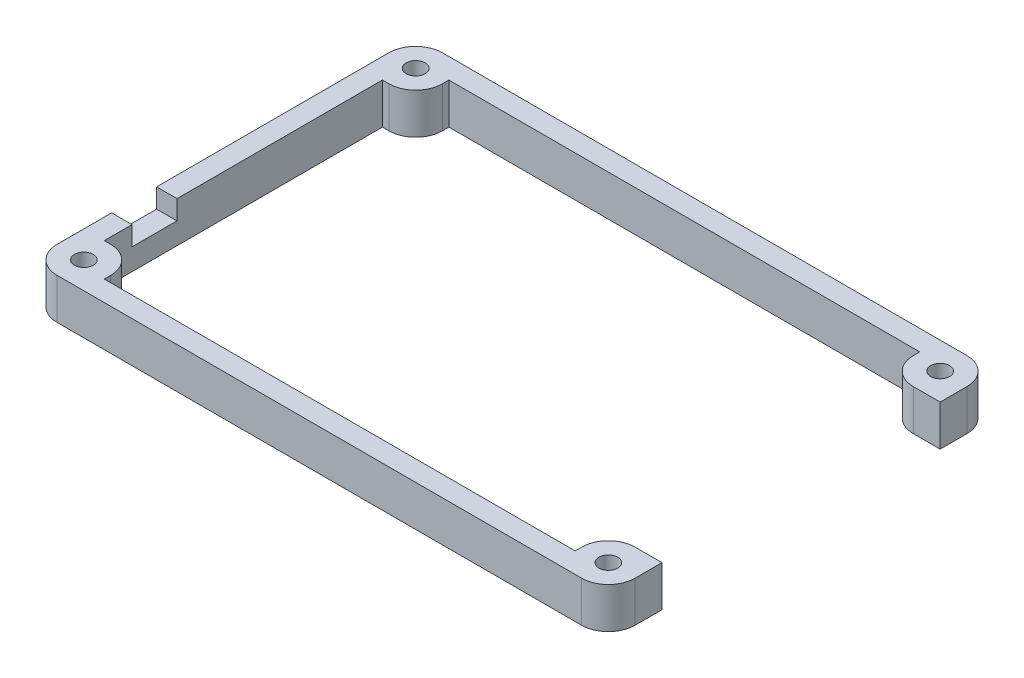
SolidWorks part; units mm, degrees
material "Rubber"
ref_plane "Front" through (0, 0, 0) normal (0, 0, 1) x (1, 0, 0)
ref_plane "Top" through (0, 0, 0) normal (0, 1, 0) x (1, 0, 0)
ref_plane "Right" through (0, 0, 0) normal (1, 0, 0) x (0, 0, -1)
sketch "Sketch1" plane through (0, 0, 0) normal (0, 1, 0) x (1, 0, 0)
  line L0 (-45, 0) -> (45, 0) construction
  line L1 (-45, 30) -> (45, 30) construction
  line L2 (-45, 30) -> (-45, -30) construction
  line L3 (-45, -30) -> (45, -30) construction
  line L4 (45, 30) -> (45, -30) construction
  line L5 (0, -30) -> (0, 30) construction
  line L6 (41.825, 26.825) -> (41.825, -26.825) construction
  line L7 (-41.825, -26.825) -> (41.825, -26.825) construction
  line L8 (-41.825, 26.825) -> (-41.825, -26.825) construction
  line L9 (-41.825, 26.825) -> (41.825, 26.825) construction
  line L10 (40.825, 25.825) -> (40.825, -25.825) construction
  line L11 (-40.825, -25.825) -> (40.825, -25.825) construction
  line L12 (-40.825, 25.825) -> (-40.825, -25.825) construction
  line L13 (-40.825, 25.825) -> (40.825, 25.825) construction
  line L14 (40.825, 21.65) -> (45, 21.65) construction
  line L15 (40.825, -21.65) -> (45, -21.65) construction
  line L16 (36.65, -25.825) -> (36.65, -30) construction
  line L17 (-36.65, -25.825) -> (-36.65, -30) construction
  line L18 (-40.825, -21.65) -> (-45, -21.65) construction
  line L19 (-36.65, 25.825) -> (-36.65, 30) construction
  line L20 (-40.825, 21.65) -> (-45, 21.65) construction
  line L21 (36.65, 25.825) -> (36.65, 30) construction
  line L22 (40.825, -25.825) -> (41.825, -25.825) construction
  circle A0 centre (-40.825, -25.825) radius 1 construction
  circle A1 centre (40.825, -25.825) radius 1 construction
  circle A2 centre (40.825, 25.825) radius 1 construction
  circle A3 centre (-40.825, 25.825) radius 1 construction
  circle A4 centre (40.825, -25.825) radius 4.175 construction
  circle A5 centre (40.825, 25.825) radius 4.175 construction
  circle A6 centre (-40.825, 25.825) radius 4.175 construction
  circle A7 centre (-40.825, -25.825) radius 4.175 construction
  dimension "D1" = 90
  dimension "D2" = 60
  dimension "D4" = 1
  dimension "D3" = 3.175
sketch "Sketch2" plane through (0, 0, 0) normal (0, 1, 0) x (1, 0, 0)
  line L0 (-45, 30) -> (-45, -30) construction
  line L1 (-45, -30) -> (45, -30) construction
  line L2 (45, 30) -> (45, -30) construction
  line L3 (-45, 30) -> (45, 30) construction
  line L4 (40.825, 21.65) -> (45, 21.65) construction
  line L5 (36.65, 25.825) -> (36.65, 30) construction
  line L6 (-36.65, 25.825) -> (-36.65, 30) construction
  line L7 (-40.825, 21.65) -> (-45, 21.65) construction
  line L8 (-36.65, -25.825) -> (-36.65, -30) construction
  line L9 (-40.825, -21.65) -> (-45, -21.65) construction
  line L10 (36.65, -25.825) -> (36.65, -30) construction
  line L11 (40.825, -21.65) -> (45, -21.65) construction
  line L16 (-45, 25.825) -> (-45, -25.825)
  line L17 (-40.825, -30) -> (40.825, -30)
  line L18 (45, 25.825) -> (45, -25.825)
  line L19 (-40.825, 30) -> (40.825, 30)
  line L20 (40.825, 21.65) -> (41.825, 21.65)
  line L21 (36.65, 25.825) -> (36.65, 26.825)
  line L22 (-36.65, 25.825) -> (-36.65, 26.825)
  line L23 (-40.825, 21.65) -> (-41.825, 21.65)
  line L24 (-36.65, -25.825) -> (-36.65, -26.825)
  line L25 (-40.825, -21.65) -> (-41.825, -21.65)
  line L26 (36.65, -25.825) -> (36.65, -26.825)
  line L27 (40.825, -21.65) -> (41.825, -21.65)
  line L28 (41.825, 26.825) -> (41.825, -26.825) construction
  line L29 (-36.65, -26.825) -> (36.65, -26.825)
  line L30 (-41.825, 26.825) -> (41.825, 26.825) construction
  line L31 (-41.825, 26.825) -> (-41.825, -26.825) construction
  line L32 (-36.65, 26.825) -> (36.65, 26.825)
  line L33 (-41.825, 21.65) -> (-41.825, -21.65)
  line L34 (41.825, 21.65) -> (41.825, -21.65)
  line L35 (-41.825, -26.825) -> (41.825, -26.825) construction
  circle A0 centre (40.825, 25.825) radius 4.175 construction
  circle A1 centre (40.825, 25.825) radius 1 construction
  circle A2 centre (-40.825, 25.825) radius 4.175 construction
  circle A3 centre (-40.825, 25.825) radius 1 construction
  circle A4 centre (-40.825, -25.825) radius 4.175 construction
  circle A5 centre (40.825, -25.825) radius 4.175 construction
  arc A6 (45, 25.825) -> (40.825, 30) centre (40.825, 25.825) ccw
  circle A7 centre (40.825, 25.825) radius 1 construction
  arc A8 (-40.825, 30) -> (-45, 25.825) centre (-40.825, 25.825) ccw
  circle A9 centre (-40.825, 25.825) radius 1 construction
  arc A10 (-36.65, -25.825) -> (-40.825, -21.65) centre (-40.825, -25.825) ccw
  arc A11 (40.825, -21.65) -> (36.65, -25.825) centre (40.825, -25.825) ccw
  circle A12 centre (-40.825, -25.825) radius 1 construction
  circle A13 centre (40.825, -25.825) radius 1 construction
  circle A14 centre (-40.825, -25.825) radius 1 construction
  circle A15 centre (40.825, -25.825) radius 1 construction
  arc A16 (-40.825, 21.65) -> (-36.65, 25.825) centre (-40.825, 25.825) ccw
  arc A17 (-45, -25.825) -> (-40.825, -30) centre (-40.825, -25.825) ccw
  arc A18 (40.825, -30) -> (45, -25.825) centre (40.825, -25.825) ccw
  arc A19 (36.65, 25.825) -> (40.825, 21.65) centre (40.825, 25.825) ccw
extrude "Boss-Extrude3" add sketch "Sketch2" along normal blind 6.35
sketch "Antenna Hole Size" plane through (-45, 0, 0) normal (-1, 0, 0) x (0, 0, 1)
  line L0 (13.825, 6.35) -> (25.825, 6.35) construction
  line L1 (25.825, 6.35) -> (25.825, 0) construction
  line L3 (10.325, 9.35) -> (17.325, 9.35)
  line L4 (10.325, 9.35) -> (10.325, 3.35)
  line L5 (10.325, 3.35) -> (17.325, 3.35)
  line L6 (17.325, 9.35) -> (17.325, 3.35)
  line L7 (10.325, 9.35) -> (17.325, 3.35) construction
  line L8 (10.325, 3.35) -> (17.325, 9.35) construction
  dimension "D1" = 12
  dimension "D2" = 6
  dimension "D3" = 7
extrude "Cut-Extrude3" cut sketch "Antenna Hole Size" against normal up to surface (3.175 mm away) up to face at (-41.825, 3.175, 0)
sketch "Sketch7" plane through (0, 0, 0) normal (0, -1, 0) x (1, 0, 0)
  circle A0 centre (-40.825, -25.825) radius 1.4732
  circle A1 centre (-40.825, 25.825) radius 1.4732
  circle A2 centre (40.825, 25.825) radius 1.4732
  circle A3 centre (40.825, -25.825) radius 1.4732
  dimension "D1" = 2.9464
  dimension "D2" = 2.9464
  dimension "D3" = 2.9464
  dimension "D4" = 2.9464
extrude "Cut-Extrude4" cut sketch "Sketch7" against normal blind 10
sketch "Sketch8" plane through (0, 6.35, 0) normal (0, 1, 0) x (1, 0, 0)
  line L0 (45, -25.825) -> (45, 25.825) construction
  line L1 (45, 21.65) -> (41.825, 21.65)
  line L2 (45, 21.65) -> (45, -21.65)
  line L3 (45, -21.65) -> (41.825, -21.65)
  line L4 (41.825, 21.65) -> (41.825, -21.65)
  line L5 (45, 21.65) -> (41.825, -21.65) construction
  line L6 (45, -21.65) -> (41.825, 21.65) construction
  point P0 (43.4125, 0)
extrude "Cut-Extrude5" cut sketch "Sketch8" against normal through all
